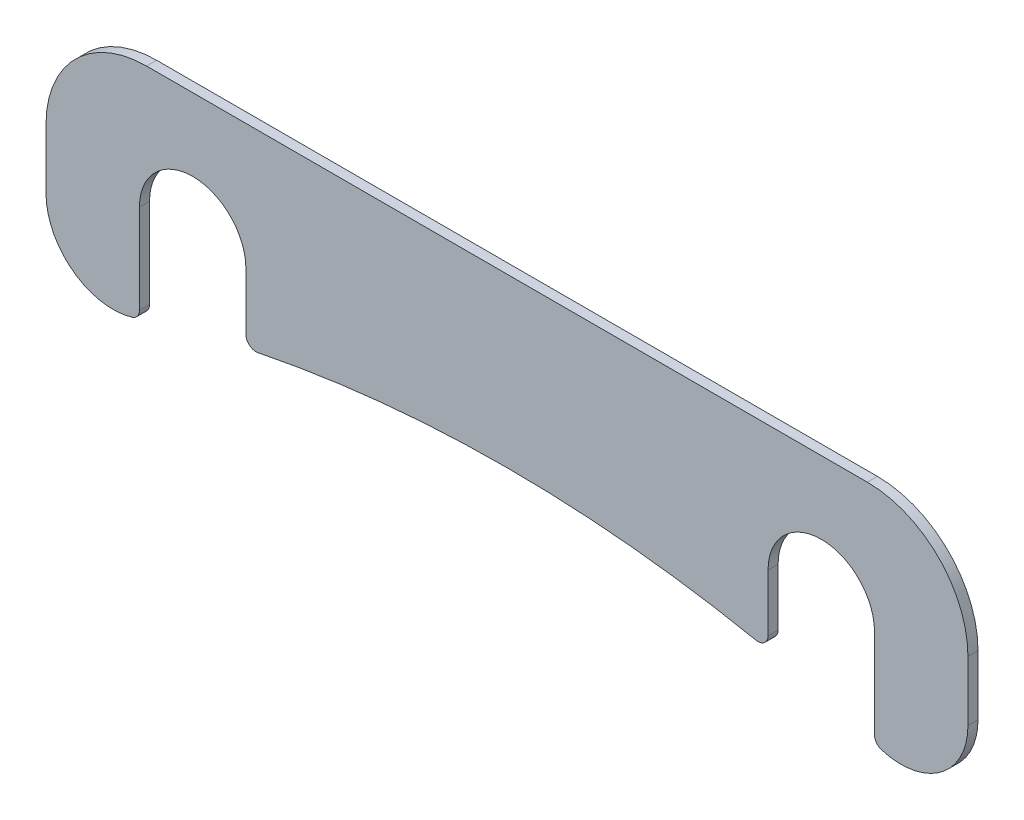
SolidWorks part; units mm, degrees
material "Plain Carbon Steel"
ref_plane "Front" through (0, 0, 0) normal (0, 0, 1) x (1, 0, 0)
ref_plane "Top" through (0, 0, 0) normal (0, 1, 0) x (1, 0, 0)
ref_plane "Right" through (0, 0, 0) normal (1, 0, 0) x (0, 0, -1)
sketch "Sketch1" plane through (0, 0, 0) normal (0, 0, 1) x (1, 0, 0)
  line L0 (-23.8125, 0) -> (23.8125, 0) construction
  line L1 (-27.305, 9.525) -> (27.305, 9.525)
  line L2 (-34.925, 1.905) -> (-34.925, -2.6368)
  line L3 (34.925, 1.905) -> (34.925, -2.6368)
  line L4 (-27.8448, 0) -> (-27.8448, -7.3359)
  line L5 (-19.7802, 0) -> (-19.7802, -5.2515)
  line L6 (19.7803, 0) -> (19.7802, -5.2515)
  line L7 (27.8447, 0) -> (27.8447, -7.3359)
  line L8 (0, 9.525) -> (0, -3.175) construction
  arc A0 (-19.7802, 0) -> (-27.8448, 0) centre (-23.8125, 0) ccw
  arc A1 (27.8447, 0) -> (19.7803, 0) centre (23.8125, 0) ccw
  arc A2 (27.305, 9.525) -> (34.925, 1.905) centre (27.305, 1.905) cw
  arc A3 (28.3339, -7.4868) -> (27.8447, -7.3359) centre (0, -98.425) ccw
  arc A4 (-27.305, 9.525) -> (-34.925, 1.905) centre (-27.305, 1.905) ccw
  arc A5 (-34.925, -2.6368) -> (-28.3339, -7.4868) centre (-29.845, -2.6368) ccw
  arc A6 (28.3339, -7.4868) -> (34.925, -2.6368) centre (29.845, -2.6368) ccw
  arc A7 (-27.8448, -7.3359) -> (-28.3339, -7.4868) centre (0, -98.425) ccw
  arc A8 (19.7802, -5.2515) -> (-19.7802, -5.2515) centre (0, -98.425) ccw
  point P10 (0, -3.175)
  point P11 (0, 9.525)
  point P23 (34.925, 9.525)
  point P26 (-34.925, 9.525)
  dimension "D1" = 8.0645
  dimension "D2" = 47.625
  dimension "D3" = 69.85
  dimension "D5" = 190.5
  dimension "D7" = 7.62
  dimension "D8" = 10.16
  dimension "D9" = 10.16
  dimension "D4" = 12.7
  dimension "D6" = 9.525
extrude "Boss-Extrude1" add sketch "Sketch1" along normal blind 0.762
fillet "Fillet1" radius 0.762 4 edges at (27.8447, -7.3359, 0.381) (19.7802, -5.2515, 0.381) (-19.7802, -5.2515, 0.381) (-27.8448, -7.3359, 0.381)
